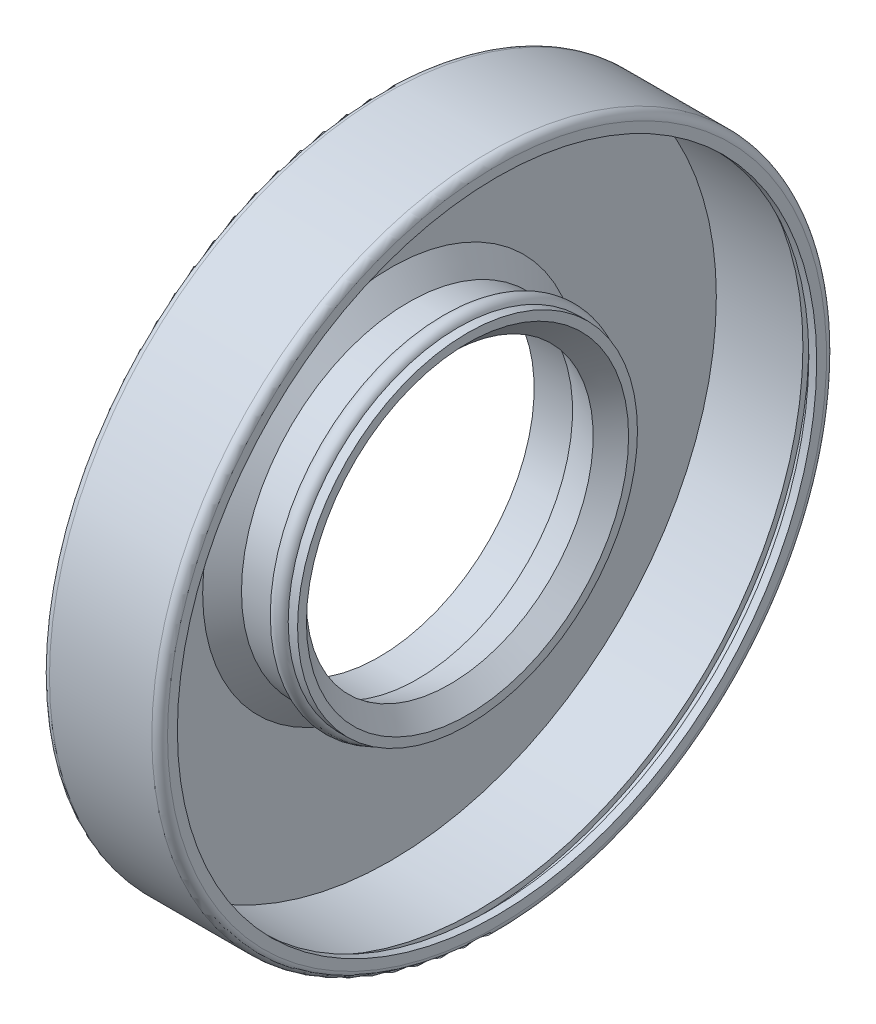
SolidWorks part; units mm, degrees
ref_plane "Plan1" through (0, 0, 0) normal (0, 0, 1) x (1, 0, 0)
ref_plane "Plan2" through (0, 0, 0) normal (0, 1, 0) x (1, 0, 0)
ref_plane "Plan3" through (0, 0, 0) normal (1, 0, 0) x (0, 0, -1)
sketch "Esquisse1" plane through (0, 0, 0) normal (0, 1, 0) x (1, 0, 0)
  line L0 (0, 0) -> (5.8333, 0) construction
  line L1 (0, 9.2) -> (0, 19.5333)
  line L2 (0.4667, 20) -> (6.5333, 20)
  line L3 (5.8333, 19.3) -> (5.8333, 19.65)
  line L4 (5.8333, 19.3) -> (0.7, 19.3)
  line L5 (0.7, 19.3) -> (0.7, 11.1513)
  line L6 (2.2768, 9.2) -> (0, 9.2)
  line L9 (5.8333, 19.65) -> (6.5333, 19.65)
  line L11 (6.5333, 19.65) -> (6.5333, 18.95)
  line L12 (7, 18.95) -> (7, 19.5333)
  line L13 (6.5333, 18.95) -> (7, 18.95)
  line L14 (2.2768, 9.2) -> (4.2, 8.5)
  line L15 (4.2, 8.5) -> (5.25, 9.55)
  line L16 (5.25, 9.55) -> (5.25, 10.075)
  line L17 (5.25, 10.075) -> (4.695, 10.075)
  line L18 (0.7, 11.1513) -> (1.75, 9.9)
  line L22 (1.75, 9.9) -> (3.675, 9.9)
  arc A0 (0, 19.5333) -> (0.4667, 20) centre (0.4667, 19.5333) cw
  arc A1 (4.695, 10.075) -> (3.675, 9.9) centre (4.2, 9.9) ccw
  arc A2 (6.5333, 20) -> (7, 19.5333) centre (6.5333, 19.5333) cw
  point P13 (0, 20)
  point P22 (7, 20)
  dimension "r" = 0.4667
  dimension "l" = 1.05
  dimension "D1" = 130
  dimension "De" = 20
  dimension "b" = 7
  dimension "e" = 0.7
  dimension "D7" = 45
  dimension "D6" = 20
  dimension "Di" = 8.5
  dimension "pl" = 5.25
  dimension "h" = 0.175
revolve "Base-Révolution" add sketch "Esquisse1" angle 360 about L0
sketch "Esquisse2" plane through (0, 0, 0) normal (-1, 0, 0) x (0, 0, 1)
  line L0 (0, 0) -> (9.2, 0) construction
  line L1 (9.2, 0) -> (9.55, 0) construction
  circle A0 centre (0, 0) radius 9.2 construction
  circle A2 centre (0, 0) radius 9.2 construction
  circle A3 centre (0, 0) radius 9.55
split line "Ligne de séparation1"
equation "\"e@Esquisse1\" = \"b@Esquisse1\"/10"
equation "\"i@Esquisse1\"=\"e@Esquisse1\"/2"
equation "\"r@Esquisse1\"=\"e@Esquisse1\"*2/3"
equation "\"l@Esquisse1\"=\"i@Esquisse1\"*3"
equation "\"pl@Esquisse1\"=\"b@Esquisse1\"*3/4"
equation "\"h@Esquisse1\"=\"i@Esquisse1\"/2"
